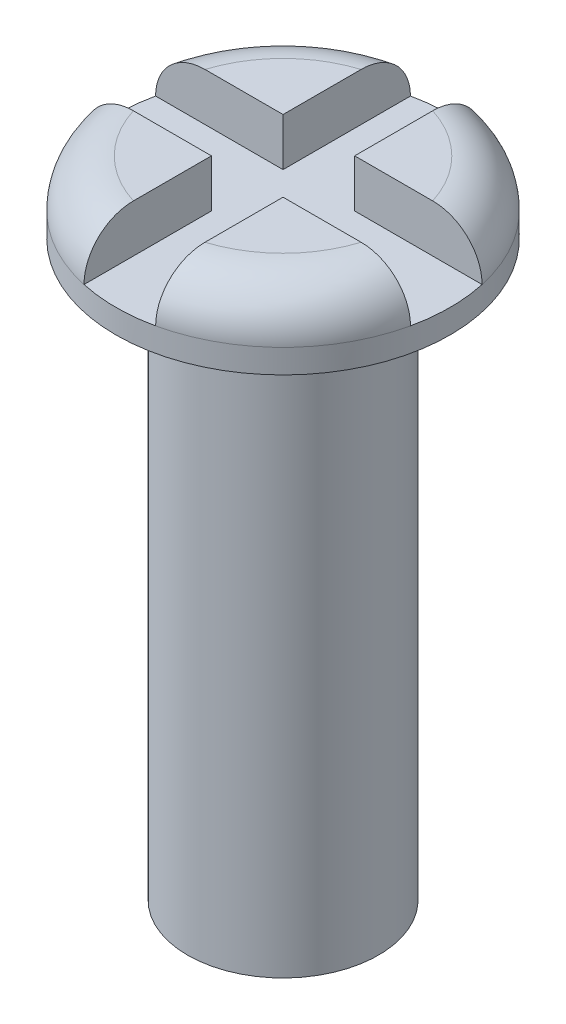
SolidWorks part; units mm, degrees
ref_plane "前视基准面" through (0, 0, 0) normal (0, 0, 1) x (1, 0, 0)
ref_plane "上视基准面" through (0, 0, 0) normal (0, 1, 0) x (1, 0, 0)
ref_plane "右视基准面" through (0, 0, 0) normal (1, 0, 0) x (0, 0, -1)
sketch "草图1" plane through (0, 0, 0) normal (0, 1, 0) x (1, 0, 0)
  circle A0 centre (0, 0) radius 1
  dimension "D1" = 2
extrude "拉伸1" add sketch "草图1" along normal blind 6
sketch "草图2" plane through (0, 6, 0) normal (0, 1, 0) x (-1, 0, 0)
  circle A0 centre (0, 0) radius 1.75
  dimension "D1" = 3.5
extrude "拉伸2" add sketch "草图2" along normal blind 0.75
fillet "圆角1" radius 0.5 1 edges at (0, 6.75, 1.75)
sketch "草图3" plane through (0, 6.75, 0) normal (0, 1, 0) x (-1, 0, 0)
  line L0 (4.0624, 0) -> (-4.2778, 0) construction
  line L1 (0, -3.5166) -> (0, 3.738) construction
  line L3 (3.5023, -0.375) -> (-3.5023, -0.375)
  line L4 (3.5023, -0.375) -> (3.5023, 0.375)
  line L5 (3.5023, 0.375) -> (-3.5023, 0.375)
  line L6 (-3.5023, -0.375) -> (-3.5023, 0.375)
  dimension "D1" = 0.75
extrude "切除-拉伸1" cut sketch "草图3" against normal blind 0.5
sketch "草图4" plane through (0, 6.75, 0) normal (0, 1, 0) x (-1, 0, 0)
  line L0 (0, -3.8639) -> (0, 3.6765) construction
  line L1 (1.7727, 0) -> (-1.7019, 0) construction
  line L2 (0.375, -1.875) -> (-0.375, -1.875)
  line L3 (0.375, -1.875) -> (0.375, 1.875)
  line L4 (0.375, 1.875) -> (-0.375, 1.875)
  line L5 (-0.375, -1.875) -> (-0.375, 1.875)
  dimension "D1" = 0.75
  dimension "D2" = 3.75
extrude "切除-拉伸2" cut sketch "草图4" against normal blind 0.5
